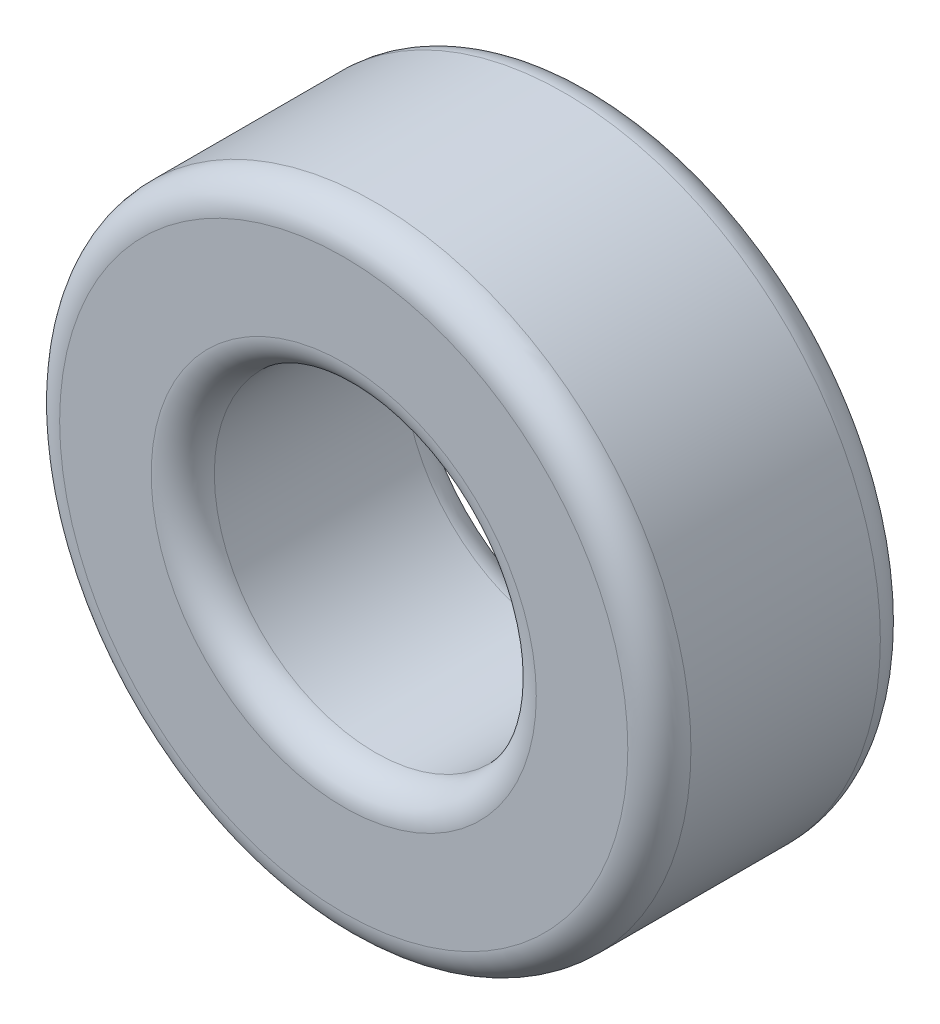
SolidWorks part; units mm, degrees
material "Nylon 101"
ref_plane "Front Plane" through (0, 0, 0) normal (0, 0, 1) x (1, 0, 0)
ref_plane "Top Plane" through (0, 0, 0) normal (0, 1, 0) x (1, 0, 0)
ref_plane "Right Plane" through (0, 0, 0) normal (1, 0, 0) x (0, 0, -1)
sketch "Sketch1" plane through (0, 0, 0) normal (0, 0, 1) x (1, 0, 0)
  circle A0 centre (0, 0) radius 12.7
  circle A1 centre (0, 0) radius 6.477
  dimension "D1" = 25.4
  dimension "D2" = 12.954
extrude "Boss-Extrude1" add sketch "Sketch1" along normal blind 10.16
fillet "Fillet1" radius 1.27 4 edges at (12.7, 0, 0) (6.477, 0, 0) (6.477, 0, 10.16) (12.7, 0, 10.16)
